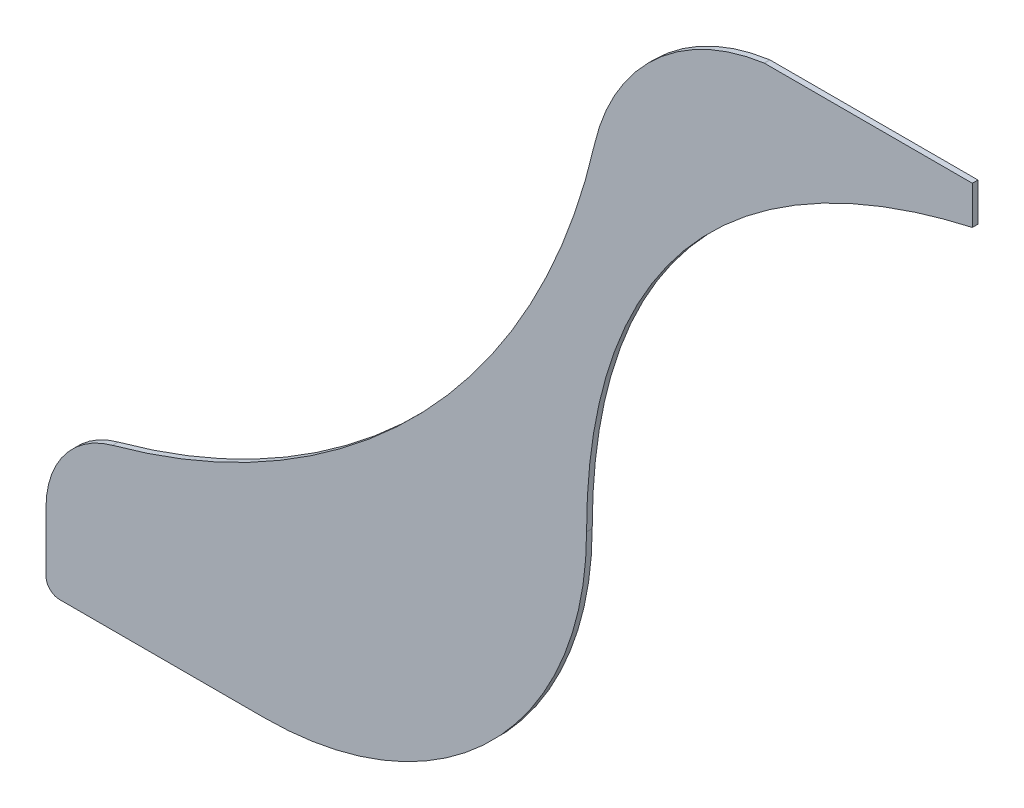
SolidWorks part; units mm, degrees
ref_plane "Front Plane" through (0, 0, 0) normal (0, 0, 1) x (1, 0, 0)
ref_plane "Top Plane" through (0, 0, 0) normal (0, 1, 0) x (1, 0, 0)
ref_plane "Right Plane" through (0, 0, 0) normal (1, 0, 0) x (0, 0, -1)
sketch "Sketch1" plane through (0, 0, 0) normal (0, 0, 1) x (1, 0, 0)
  line L15 (771.9038, 164.4658) -> (771.9038, 186.0558)
  line L16 (771.9038, 186.0558) -> (654.5558, 186.0558)
  line L17 (249.5716, -233.3505) -> (249.5716, -266.9601)
  line L20 (0, 0) -> (82.8917, 0) construction
  line L21 (0, 0) -> (0, -86.4487) construction
  line L25 (554.3716, -92.9115) -> (554.3716, -243.3961) construction
  line L26 (257.1916, -274.5801) -> (372.703, -274.5801)
  line L27 (487.9505, -105.8899) -> (481.4591, -111.1185) construction
  line L31 (482.8117, -113.0198) -> (487.9505, -105.8899) construction
  line L32 (481.4591, -111.1185) -> (482.8117, -113.0198) construction
  line L33 (487.9505, -105.8899) -> (333.8328, -217.863) construction
  line L40 (361.6164, -231.6548) -> (133.988, -252.7091) construction
  line L41 (157.3315, -273.5734) -> (-70.4948, -254.7805) construction
  line L42 (553.6355, -2.6046) -> (554.0717, -1.4808) construction
  line L43 (554.0717, -1.4808) -> (553.3904, -2.3989) construction
  line L48 (553.3904, -2.3989) -> (553.6355, -2.6046) construction
  line L49 (553.513, -2.5017) -> (471.8789, -99.7894) construction
  arc A2 (654.5558, 186.0558) -> (558.8, 98.352) centre (670.215, 72.8335) ccw
  arc A3 (287.0828, -184.3195) -> (558.8, 98.352) centre (187.4168, 183.4137) ccw
  arc A4 (287.0828, -184.3195) -> (249.5716, -233.3505) centre (300.3716, -233.3505) ccw
  arc A5 (249.5716, -266.9601) -> (257.1916, -274.5801) centre (257.1916, -266.9601) ccw
  arc A7 (554.3716, -92.9115) -> (372.703, -274.5801) centre (372.703, -92.9115) cw
  spline S0 degree 3 poles (360.3362, -232.1476) (361.944, -231.5594) (360.2733, -231.9279) (358.8705, -232.1286) (355.491, -232.7497) (351.3118, -233.4654) (345.8288, -234.3937) (339.3319, -235.4503) (331.8137, -236.6267) (323.3898, -237.8749) (314.1481, -239.1645) (304.196, -240.4529) (293.645, -241.7102) (282.6109, -242.9031) (271.2144, -244.0118) (259.5796, -245.0173) (247.8327, -245.923) (236.1052, -246.7089) (224.5878, -247.4466) (213.3874, -247.9449) (202.6055, -248.1613) (192.2857, -248.184) (182.5214, -248.0635) (173.413, -247.8762) (165.0492, -247.6957) (157.5243, -247.5827) (150.9198, -247.5968) (145.3176, -247.8045) (140.7752, -248.2212) (137.3462, -248.9332) (134.9534, -249.8477) (133.6053, -251.5229) (134.1931, -253.5982) (136.0729, -255.3852) (139.0627, -257.3468) (143.3055, -259.3644) (148.7486, -261.4241) (155.3647, -263.3995) (163.0752, -265.2124) (171.7927, -266.7481) (181.4066, -267.9166) (191.7956, -268.6246) (202.8233, -268.8006) (214.344, -268.4024) (226.142, -267.3648) (238.0677, -265.8064) (250.0128, -263.9526) (261.9011, -261.7778) (273.6057, -259.3395) (284.9982, -256.6886) (295.9553, -253.8811) (306.362, -250.9812) (316.1121, -248.0592) (325.1026, -245.1817) (333.2481, -242.4287) (340.4703, -239.8598) (346.6777, -237.559) (351.8912, -235.562) (355.8426, -233.9905) (359.046, -232.7314) (360.3362, -232.1476) (361.944, -231.5594) (360.2733, -231.9279) knots -0.012273 -0.005484 -0.001375 0 0.001366 0.005489 0.012269 0.02165 0.033497 0.04769 0.06403 0.082338 0.102396 0.123959 0.146791 0.170641 0.19524 0.220332 0.245646 0.27091 0.295825 0.31977 0.342911 0.365083 0.386049 0.405629 0.423597 0.43978 0.453966 0.466008 0.475784 0.483219 0.48846 0.492078 0.495706 0.500976 0.508553 0.518608 0.53108 0.545907 0.56292 0.581928 0.60273 0.625094 0.648778 0.673537 0.699099 0.724814 0.750772 0.776731 0.802428 0.827555 0.851851 0.875071 0.896936 0.917223 0.935694 0.952169 0.966419 0.978318 0.987727 0.994516 0.998625 1 1.001366 1.005489 1.012269 only from (393.8383, -231.1805) to (393.8383, -231.1805) construction
  spline S1 degree 3 poles (155.9851, -273.8364) (157.6707, -273.5362) (155.9614, -273.6091) (154.545, -273.5632) (151.109, -273.588) (146.869, -273.5671) (141.3082, -273.5292) (134.7264, -273.4415) (127.1182, -273.2946) (118.6055, -273.0609) (109.2803, -272.7261) (99.2556, -272.2668) (88.6466, -271.6729) (77.573, -270.9316) (66.1571, -270.0445) (54.5244, -269.0143) (42.7988, -267.8665) (31.1129, -266.6039) (19.6424, -265.3305) (8.5257, -263.8763) (-2.1301, -262.2171) (-12.2969, -260.4475) (-21.892, -258.6332) (-30.8295, -256.8671) (-39.0349, -255.237) (-46.4259, -253.8191) (-52.9324, -252.6861) (-58.4856, -251.9178) (-63.0313, -251.5394) (-66.5319, -251.6451) (-69.0472, -252.1302) (-70.6657, -253.5459) (-70.4472, -255.6917) (-68.9062, -257.778) (-66.3025, -260.229) (-62.4745, -262.9527) (-57.4718, -265.9263) (-51.2992, -269.0205) (-44.0206, -272.1448) (-35.7023, -275.171) (-26.4373, -277.9912) (-16.3291, -280.4924) (-5.4995, -282.5807) (5.9153, -284.1891) (17.7142, -285.2159) (29.7294, -285.7521) (41.8149, -286.0007) (53.9003, -285.9233) (65.8505, -285.5546) (77.5302, -284.9222) (88.8084, -284.06) (99.5605, -283.0113) (109.6699, -281.8268) (119.0235, -280.5542) (127.5233, -279.2575) (135.0819, -277.9817) (141.5945, -276.7938) (147.0755, -275.7324) (151.2398, -274.8709) (154.6131, -274.1873) (155.9851, -273.8364) (157.6707, -273.5362) (155.9614, -273.6091) knots -0.012273 -0.005484 -0.001375 0 0.001366 0.005489 0.012269 0.02165 0.033497 0.04769 0.06403 0.082338 0.102396 0.123959 0.146791 0.170641 0.19524 0.220332 0.245646 0.27091 0.295825 0.31977 0.342911 0.365083 0.386049 0.405629 0.423597 0.43978 0.453966 0.466008 0.475784 0.483219 0.48846 0.492078 0.495706 0.500976 0.508553 0.518608 0.53108 0.545907 0.56292 0.581928 0.60273 0.625094 0.648778 0.673537 0.699099 0.724814 0.750772 0.776731 0.802428 0.827555 0.851851 0.875071 0.896936 0.917223 0.935694 0.952169 0.966419 0.978318 0.987727 0.994516 0.998625 1 1.001366 1.005489 1.012269 only from (157.3315, -273.5734) to (157.3315, -273.5734) construction
  spline S2 degree 3 poles (554.3716, -92.9115) (554.3716, 52.3079) (646.1726, 136.1939) (771.9038, 164.4658) knots 0 0 0 0 1 1 1 1
  spline S3 degree 3 poles (360.3362, -232.1476) (361.944, -231.5594) (360.2733, -231.9279) (358.8705, -232.1286) (355.491, -232.7497) (351.3118, -233.4654) (345.8288, -234.3937) (339.3319, -235.4503) (331.8137, -236.6267) (323.3898, -237.8749) (314.1481, -239.1645) (304.196, -240.4529) (293.645, -241.7102) (282.6109, -242.9031) (271.2144, -244.0118) (259.5796, -245.0173) (247.8327, -245.923) (236.1052, -246.7089) (224.5878, -247.4466) (213.3874, -247.9449) (202.6055, -248.1613) (192.2857, -248.184) (182.5214, -248.0635) (173.413, -247.8762) (165.0492, -247.6957) (157.5243, -247.5827) (150.9198, -247.5968) (145.3176, -247.8045) (140.7752, -248.2212) (137.3462, -248.9332) (134.9534, -249.8477) (133.6053, -251.5229) (134.1931, -253.5982) (136.0729, -255.3852) (139.0627, -257.3468) (143.3055, -259.3644) (148.7486, -261.4241) (155.3647, -263.3995) (163.0752, -265.2124) (171.7927, -266.7481) (181.4066, -267.9166) (191.7956, -268.6246) (202.8233, -268.8006) (214.344, -268.4024) (226.142, -267.3648) (238.0677, -265.8064) (250.0128, -263.9526) (261.9011, -261.7778) (273.6057, -259.3395) (284.9982, -256.6886) (295.9553, -253.8811) (306.362, -250.9812) (316.1121, -248.0592) (325.1026, -245.1817) (333.2481, -242.4287) (340.4703, -239.8598) (346.6777, -237.559) (351.8912, -235.562) (355.8426, -233.9905) (359.046, -232.7314) (360.3362, -232.1476) (361.944, -231.5594) (360.2733, -231.9279) knots -0.012273 -0.005484 -0.001375 0 0.001366 0.005489 0.012269 0.02165 0.033497 0.04769 0.06403 0.082338 0.102396 0.123959 0.146791 0.170641 0.19524 0.220332 0.245646 0.27091 0.295825 0.31977 0.342911 0.365083 0.386049 0.405629 0.423597 0.43978 0.453966 0.466008 0.475784 0.483219 0.48846 0.492078 0.495706 0.500976 0.508553 0.518608 0.53108 0.545907 0.56292 0.581928 0.60273 0.625094 0.648778 0.673537 0.699099 0.724814 0.750772 0.776731 0.802428 0.827555 0.851851 0.875071 0.896936 0.917223 0.935694 0.952169 0.966419 0.978318 0.987727 0.994516 0.998625 1 1.001366 1.005489 1.012269 only from (361.6164, -231.6548) to (361.6164, -231.6548) construction
  spline S4 degree 3 poles (481.4591, -111.1185) (479.9311, -112.3492) (478.4019, -113.5784) (475.3352, -116.0262) (473.7986, -117.246) (469.1777, -120.8915) (466.0826, -123.304) (456.757, -130.4797) (450.4831, -135.1801) (437.8195, -144.4114) (431.4292, -148.9413) (418.5478, -157.8533) (412.0565, -162.2351) (402.2737, -168.7406) (399.0036, -170.8958) (394.0979, -174.1275) (392.4619, -175.2038) (389.175, -177.3342) (387.5236, -178.3877) (382.5482, -181.5174) (379.2036, -183.5633) (372.4743, -187.5963) (369.0895, -189.5834) (362.305, -193.5354) (358.9052, -195.4992) (353.8273, -198.4802) (352.1385, -199.4801) (348.7793, -201.5097) (347.1085, -202.5387) (343.8044, -204.6577) (342.1701, -205.7458) (339.7816, -207.48) (338.9942, -208.0762) (337.4686, -209.318) (336.7278, -209.9619) (335.6833, -210.9983) (335.346, -211.3551) (334.7053, -212.1046) (334.4006, -212.5011) (333.8582, -213.3311) (333.6208, -213.7647) (333.3563, -214.4654) (333.2841, -214.7056) (333.1809, -215.1905) (333.1492, -215.4365) (333.1362, -215.938) (333.1557, -216.1871) (333.25, -216.6728) (333.3249, -216.9136) (333.5217, -217.3726) (333.6422, -217.5894) (333.9253, -217.9984) (334.0895, -218.191) (334.4432, -218.5399) (334.6338, -218.6983) (335.0376, -218.9892) (335.2513, -219.122) (335.9056, -219.479) (336.3648, -219.6653) (337.3113, -219.9741) (337.7948, -220.0953) (338.7669, -220.2879) (339.2572, -220.3605) (340.2437, -220.4722) (340.7405, -220.5104) (341.7293, -220.5596) (342.2227, -220.5711) (343.7004, -220.5737) (344.6823, -220.5329) (346.6415, -220.3924) (347.6188, -220.2916) (349.5696, -220.0431) (350.5432, -219.8949) (352.4873, -219.5579) (353.4579, -219.3692) (356.3485, -218.7527) (358.254, -218.2747) (363.9171, -216.6764) (367.6222, -215.3936) (373.0942, -213.2047) (374.9065, -212.4291) (378.4909, -210.799) (380.2588, -209.9467) (385.4943, -207.286) (388.8944, -205.3743) (395.5325, -201.3035) (398.7707, -199.1446) (405.0966, -194.597) (408.178, -192.1986) (412.7496, -188.524) (414.2635, -187.2839) (417.2706, -184.772) (418.7629, -183.5013) (426.1552, -177.0934) (431.8654, -171.7806) (442.9379, -160.8369) (448.2998, -155.2054) (458.7045, -143.6503) (463.7467, -137.7263) (471.0747, -128.6248) (473.4778, -125.5548) (477.0229, -120.8953) (478.1947, -119.333) (480.5181, -116.19) (481.6675, -114.6073) (482.8117, -113.0198) knots 0 0 0 0 0.015625 0.015625 0.03125 0.03125 0.0625 0.0625 0.125 0.125 0.1875 0.1875 0.25 0.25 0.28125 0.28125 0.296875 0.296875 0.3125 0.3125 0.34375 0.34375 0.375 0.375 0.40625 0.40625 0.421875 0.421875 0.4375 0.4375 0.453125 0.453125 0.460938 0.460938 0.46875 0.46875 0.472656 0.472656 0.476563 0.476563 0.480469 0.480469 0.482422 0.482422 0.484375 0.484375 0.486328 0.486328 0.488281 0.488281 0.490234 0.490234 0.492188 0.492188 0.494141 0.494141 0.496094 0.496094 0.5 0.5 0.503906 0.503906 0.507813 0.507813 0.511719 0.511719 0.515625 0.515625 0.523438 0.523438 0.53125 0.53125 0.539063 0.539063 0.546875 0.546875 0.5625 0.5625 0.59375 0.59375 0.609375 0.609375 0.625 0.625 0.65625 0.65625 0.6875 0.6875 0.71875 0.71875 0.734375 0.734375 0.75 0.75 0.8125 0.8125 0.875 0.875 0.9375 0.9375 0.96875 0.96875 0.984375 0.984375 1 1 1 1 construction
  spline S8 degree 3 poles (155.9851, -273.8364) (157.6707, -273.5362) (155.9614, -273.6091) (154.545, -273.5632) (151.109, -273.588) (146.869, -273.5671) (141.3082, -273.5292) (134.7264, -273.4415) (127.1182, -273.2946) (118.6055, -273.0609) (109.2803, -272.7261) (99.2556, -272.2668) (88.6466, -271.6729) (77.573, -270.9316) (66.1571, -270.0445) (54.5244, -269.0143) (42.7988, -267.8665) (31.1129, -266.6039) (19.6424, -265.3305) (8.5257, -263.8763) (-2.1301, -262.2171) (-12.2969, -260.4475) (-21.892, -258.6332) (-30.8295, -256.8671) (-39.0349, -255.237) (-46.4259, -253.8191) (-52.9324, -252.6861) (-58.4856, -251.9178) (-63.0313, -251.5394) (-66.5319, -251.6451) (-69.0472, -252.1302) (-70.6657, -253.5459) (-70.4472, -255.6917) (-68.9062, -257.778) (-66.3025, -260.229) (-62.4745, -262.9527) (-57.4718, -265.9263) (-51.2992, -269.0205) (-44.0206, -272.1448) (-35.7023, -275.171) (-26.4373, -277.9912) (-16.3291, -280.4924) (-5.4995, -282.5807) (5.9153, -284.1891) (17.7142, -285.2159) (29.7294, -285.7521) (41.8149, -286.0007) (53.9003, -285.9233) (65.8505, -285.5546) (77.5302, -284.9222) (88.8084, -284.06) (99.5605, -283.0113) (109.6699, -281.8268) (119.0235, -280.5542) (127.5233, -279.2575) (135.0819, -277.9817) (141.5945, -276.7938) (147.0755, -275.7324) (151.2398, -274.8709) (154.6131, -274.1873) (155.9851, -273.8364) (157.6707, -273.5362) (155.9614, -273.6091) knots -0.012273 -0.005484 -0.001375 0 0.001366 0.005489 0.012269 0.02165 0.033497 0.04769 0.06403 0.082338 0.102396 0.123959 0.146791 0.170641 0.19524 0.220332 0.245646 0.27091 0.295825 0.31977 0.342911 0.365083 0.386049 0.405629 0.423597 0.43978 0.453966 0.466008 0.475784 0.483219 0.48846 0.492078 0.495706 0.500976 0.508553 0.518608 0.53108 0.545907 0.56292 0.581928 0.60273 0.625094 0.648778 0.673537 0.699099 0.724814 0.750772 0.776731 0.802428 0.827555 0.851851 0.875071 0.896936 0.917223 0.935694 0.952169 0.966419 0.978318 0.987727 0.994516 0.998625 1 1.001366 1.005489 1.012269 only from (157.3315, -273.5734) to (157.3315, -273.5734) construction
  spline S10 degree 3 poles (767.1332, 174.7585) (765.2016, 175.0673) (763.2596, 175.3235) (759.1744, 175.8228) (757.0304, 176.0564) (752.7418, 176.4889) (750.5962, 176.687) (744.1563, 177.2402) (739.8591, 177.5552) (731.2581, 178.0939) (726.9542, 178.3159) (718.3391, 178.6603) (714.0324, 178.7822) (705.4307, 178.8961) (701.1345, 178.8876) (692.5538, 178.7035) (688.2693, 178.5288) (679.7191, 177.9146) (675.454, 177.4647) (666.9484, 176.2184) (662.7077, 175.4246) (657.4232, 174.2005) (656.3659, 173.9438) (654.2603, 173.4085) (653.212, 173.13) (650.0807, 172.2617) (648.0114, 171.6392) (641.8586, 169.6382) (637.8309, 168.1255) (629.927, 164.7352) (626.0486, 162.8627) (620.3615, 159.7397) (618.4878, 158.6457) (614.7916, 156.3341) (612.9839, 155.1261) (609.4692, 152.5936) (607.7607, 151.2689) (604.4646, 148.4749) (602.876, 147.0068) (600.6146, 144.6595) (599.881, 143.8529) (598.4641, 142.1794) (597.7849, 141.3176) (596.5088, 139.5479) (595.9106, 138.6378) (594.814, 136.7546) (594.3162, 135.7811) (593.8902, 134.7622) knots 0.548291 0.548291 0.548291 0.548291 0.5625 0.5625 0.578125 0.578125 0.59375 0.59375 0.625 0.625 0.65625 0.65625 0.6875 0.6875 0.71875 0.71875 0.75 0.75 0.78125 0.78125 0.8125 0.8125 0.820313 0.820313 0.828125 0.828125 0.84375 0.84375 0.875 0.875 0.90625 0.90625 0.921875 0.921875 0.9375 0.9375 0.953125 0.953125 0.96875 0.96875 0.976563 0.976563 0.984375 0.984375 0.992188 0.992188 1 1 1 1 construction
  spline S11 degree 3 poles (593.8902, 134.7622) (593.8636, 134.6934) (593.8359, 134.6206) (593.7827, 134.4786) (593.7041, 134.2653) (593.6288, 134.0511) (593.4832, 133.6214) (593.3926, 133.3332) (593.1421, 132.4625) (593.0035, 131.8742) (592.7957, 130.6785) (592.728, 130.0751) (592.6861, 128.8714) (592.7083, 128.2689) (592.8851, 127.0621) (593.0416, 126.4765) (593.351, 125.7819) (593.419, 125.644) (593.5687, 125.3787) (593.6506, 125.2511) (593.8263, 125.0043) (593.9197, 124.8848) (594.1287, 124.6616) (594.2421, 124.5566) (594.4838, 124.3741) (594.6135, 124.2963) (594.8846, 124.1583) (595.0255, 124.0963) (595.453, 123.9388) (595.7471, 123.8685) (596.3435, 123.7593) (596.6469, 123.7244) (597.2518, 123.6809) (597.5547, 123.6719) (598.1613, 123.6757) (598.4663, 123.6888) (599.067, 123.7328) (599.3636, 123.7636) (600.2449, 123.8764) (600.8212, 123.9782) (602.5332, 124.3238) (603.6498, 124.6131) (606.952, 125.5936) (609.0929, 126.3912) (613.3234, 128.108) (615.4109, 129.0325) (619.5559, 130.9524) (621.6132, 131.9485) (625.7182, 133.9636) (627.7659, 134.9826) (631.8662, 137.0087) (633.9197, 138.0138) (640.0996, 140.9831) (644.2447, 142.9029) (650.5124, 145.6638) (652.6097, 146.5649) (656.8223, 148.3244) (658.9383, 149.183) (665.3075, 151.6825) (669.5845, 153.2445) (678.1969, 156.1718) (682.5326, 157.5358) (691.2473, 160.1183) (695.6256, 161.3387) (704.4194, 163.6543) (708.8347, 164.75) (717.7031, 166.814) (722.1596, 167.7831) (731.0926, 169.569) (735.5702, 170.3864) (744.547, 171.8713) (749.0461, 172.541) (758.0632, 173.7492) (762.5815, 174.287) (767.1175, 174.7569) (767.1253, 174.7577) (767.1332, 174.7585) knots 0 0 0 0 0.000488 0.000488 0.000977 0.001953 0.001953 0.003906 0.003906 0.007812 0.007812 0.011719 0.011719 0.015625 0.015625 0.019531 0.019531 0.020508 0.020508 0.021484 0.021484 0.022461 0.022461 0.023438 0.023438 0.024414 0.024414 0.025391 0.025391 0.027344 0.027344 0.029297 0.029297 0.03125 0.03125 0.033203 0.033203 0.035156 0.035156 0.039063 0.039063 0.046875 0.046875 0.0625 0.0625 0.078125 0.078125 0.09375 0.09375 0.109375 0.109375 0.125 0.125 0.15625 0.15625 0.171875 0.171875 0.1875 0.1875 0.21875 0.21875 0.25 0.25 0.28125 0.28125 0.3125 0.3125 0.34375 0.34375 0.375 0.375 0.40625 0.40625 0.4375 0.4375 0.437554 0.437554 0.437554 0.437554 construction
  spline S12 degree 3 poles (733.7295, 177.9362) (730.0378, 178.1558) (726.3436, 178.3403) (718.3391, 178.6603) (714.0324, 178.7822) (705.4307, 178.8961) (701.1345, 178.8876) (692.5538, 178.7035) (688.2693, 178.5288) (679.7191, 177.9146) (675.454, 177.4647) (666.9484, 176.2184) (662.7077, 175.4246) (657.4232, 174.2005) (656.3659, 173.9438) (654.2603, 173.4085) (653.212, 173.13) (650.0807, 172.2617) (648.0114, 171.6392) (641.8586, 169.6382) (637.8309, 168.1255) (629.927, 164.7352) (626.0486, 162.8627) (620.3615, 159.7397) (618.4878, 158.6457) (614.7916, 156.3341) (612.9839, 155.1261) (609.4692, 152.5936) (607.7607, 151.2689) (604.4646, 148.4749) (602.876, 147.0068) (600.6146, 144.6595) (599.881, 143.8529) (598.4641, 142.1794) (597.7849, 141.3176) (596.5088, 139.5479) (595.9106, 138.6378) (594.814, 136.7546) (594.3162, 135.7811) (593.8902, 134.7622) knots 0.62943 0.62943 0.62943 0.62943 0.65625 0.65625 0.6875 0.6875 0.71875 0.71875 0.75 0.75 0.78125 0.78125 0.8125 0.8125 0.820313 0.820313 0.828125 0.828125 0.84375 0.84375 0.875 0.875 0.90625 0.90625 0.921875 0.921875 0.9375 0.9375 0.953125 0.953125 0.96875 0.96875 0.976563 0.976563 0.984375 0.984375 0.992188 0.992188 1 1 1 1 construction
  spline S13 degree 3 poles (593.8902, 134.7622) (593.8636, 134.6934) (593.8359, 134.6206) (593.7827, 134.4786) (593.7041, 134.2653) (593.6288, 134.0511) (593.4832, 133.6214) (593.3926, 133.3332) (593.1421, 132.4625) (593.0035, 131.8742) (592.7957, 130.6785) (592.728, 130.0751) (592.6861, 128.8714) (592.7083, 128.2689) (592.8851, 127.0621) (593.0416, 126.4765) (593.351, 125.7819) (593.419, 125.644) (593.5687, 125.3787) (593.6506, 125.2511) (593.8263, 125.0043) (593.9197, 124.8848) (594.1287, 124.6616) (594.2421, 124.5566) (594.4838, 124.3741) (594.6135, 124.2963) (594.8846, 124.1583) (595.0255, 124.0963) (595.453, 123.9388) (595.7471, 123.8685) (596.3435, 123.7593) (596.6469, 123.7244) (597.2518, 123.6809) (597.5547, 123.6719) (598.1613, 123.6757) (598.4663, 123.6888) (599.067, 123.7328) (599.3636, 123.7636) (600.2449, 123.8764) (600.8212, 123.9782) (602.5332, 124.3238) (603.6498, 124.6131) (606.952, 125.5936) (609.0929, 126.3912) (613.3234, 128.108) (615.4109, 129.0325) (619.5559, 130.9524) (621.6132, 131.9485) (625.7182, 133.9636) (627.7659, 134.9826) (631.8662, 137.0087) (633.9197, 138.0138) (640.0996, 140.9831) (644.2447, 142.9029) (650.5124, 145.6638) (652.6097, 146.5649) (656.8223, 148.3244) (658.9383, 149.183) (665.3075, 151.6825) (669.5845, 153.2445) (678.1969, 156.1718) (682.5326, 157.5358) (691.2473, 160.1183) (695.6256, 161.3387) (704.4194, 163.6543) (708.8347, 164.75) (717.7031, 166.814) (722.1596, 167.7831) (728.9908, 169.1488) (731.3586, 169.6004) (733.7295, 170.0309) knots 0 0 0 0 0.000488 0.000488 0.000977 0.001953 0.001953 0.003906 0.003906 0.007812 0.007812 0.011719 0.011719 0.015625 0.015625 0.019531 0.019531 0.020508 0.020508 0.021484 0.021484 0.022461 0.022461 0.023438 0.023438 0.024414 0.024414 0.025391 0.025391 0.027344 0.027344 0.029297 0.029297 0.03125 0.03125 0.033203 0.033203 0.035156 0.035156 0.039063 0.039063 0.046875 0.046875 0.0625 0.0625 0.078125 0.078125 0.09375 0.09375 0.109375 0.109375 0.125 0.125 0.15625 0.15625 0.171875 0.171875 0.1875 0.1875 0.21875 0.21875 0.25 0.25 0.28125 0.28125 0.3125 0.3125 0.34375 0.34375 0.360295 0.360295 0.360295 0.360295 construction
  spline S14 degree 3 poles (553.3904, -2.3989) (553.3514, -2.4513) (553.1959, -2.661) (552.8463, -3.1311) (552.2656, -3.911) (551.456, -4.9947) (550.421, -6.3743) (549.1649, -8.0397) (547.6929, -9.9783) (546.0115, -12.1759) (544.1274, -14.6163) (542.0492, -17.2815) (539.7856, -20.1517) (537.347, -23.2065) (534.7448, -26.4238) (531.9922, -29.7814) (529.1029, -33.2559) (526.0934, -36.8246) (522.9806, -40.4643) (519.7838, -44.1526) (516.5241, -47.8678) (513.2232, -51.5884) (509.9058, -55.2951) (506.5941, -58.9665) (503.3226, -62.5937) (500.0506, -66.1002) (496.8119, -69.4764) (493.6374, -72.711) (490.5595, -75.7948) (487.6104, -78.7198) (484.8217, -81.4798) (482.2236, -84.0684) (479.8454, -86.4812) (477.7129, -88.7131) (475.8507, -90.7603) (474.2795, -92.619) (473.0169, -94.2862) (472.0758, -95.7608) (471.4656, -97.0465) (471.1903, -98.1573) (471.2999, -99.1287) (471.8655, -99.8712) (472.7755, -100.3144) (473.9689, -100.4903) (475.4441, -100.4222) (477.2004, -100.1094) (479.2264, -99.5471) (481.5021, -98.728) (484.0036, -97.647) (486.7026, -96.2984) (489.5694, -94.6786) (492.5721, -92.7853) (495.6783, -90.618) (498.8556, -88.1789) (502.0721, -85.4724) (505.2972, -82.5063) (508.5016, -79.291) (511.6581, -75.8404) (514.7427, -72.1717) (517.728, -68.3047) (520.6683, -64.3201) (523.5382, -60.2365) (526.326, -56.0844) (529.0181, -51.8921) (531.6034, -47.6903) (534.071, -43.509) (536.4119, -39.3792) (538.6184, -35.332) (540.6836, -31.398) (542.6024, -27.6077) (544.3701, -23.9907) (545.9839, -20.576) (547.4421, -17.3913) (548.7433, -14.4628) (549.8875, -11.8154) (550.8755, -9.4715) (551.708, -7.4517) (552.3864, -5.7738) (552.9123, -4.4526) (553.2867, -3.5002) (553.5111, -2.9253) (553.6106, -2.6688) (553.6355, -2.6046) knots 0 0 0 0 0.000751 0.002998 0.006728 0.011917 0.018533 0.026535 0.035872 0.046487 0.058313 0.071277 0.085299 0.100293 0.116166 0.13282 0.150153 0.16806 0.186431 0.205154 0.224112 0.243191 0.262273 0.281239 0.299973 0.318368 0.336314 0.3537 0.370414 0.38635 0.401402 0.415472 0.428469 0.440308 0.45092 0.460246 0.46825 0.474922 0.480304 0.484529 0.48793 0.491137 0.494783 0.499272 0.504867 0.511675 0.51972 0.528986 0.53943 0.550997 0.56362 0.577229 0.591748 0.607102 0.623214 0.640008 0.657405 0.675329 0.693699 0.712432 0.731423 0.750565 0.769746 0.788854 0.807777 0.826399 0.844608 0.86229 0.879335 0.895632 0.911077 0.925567 0.939006 0.951301 0.962367 0.972127 0.980511 0.987456 0.992913 0.99684 0.999209 1 1 1 1 construction
  point P39 (157.3315, -273.5734)
  dimension "D2" = 381
  dimension "D3" = 114.3
  dimension "D6" = 50.8
  dimension "D10" = 76.2
  dimension "D12" = 117.348
  dimension "D13" = 21.59
  dimension "D14" = 7.62
  dimension "D4" = 304.8
  dimension "D5" = 33.6096
  dimension "D8" = 144.2667
  dimension "D15" = 184.3195
  dimension "D16" = 98.352
  dimension "D17" = 186.0558
  dimension "D18" = 92.9115
  dimension "D19" = 654.5558
  dimension "D20" = 558.8
extrude "Boss-Extrude1" add sketch "Sketch1" along normal blind 3.175
